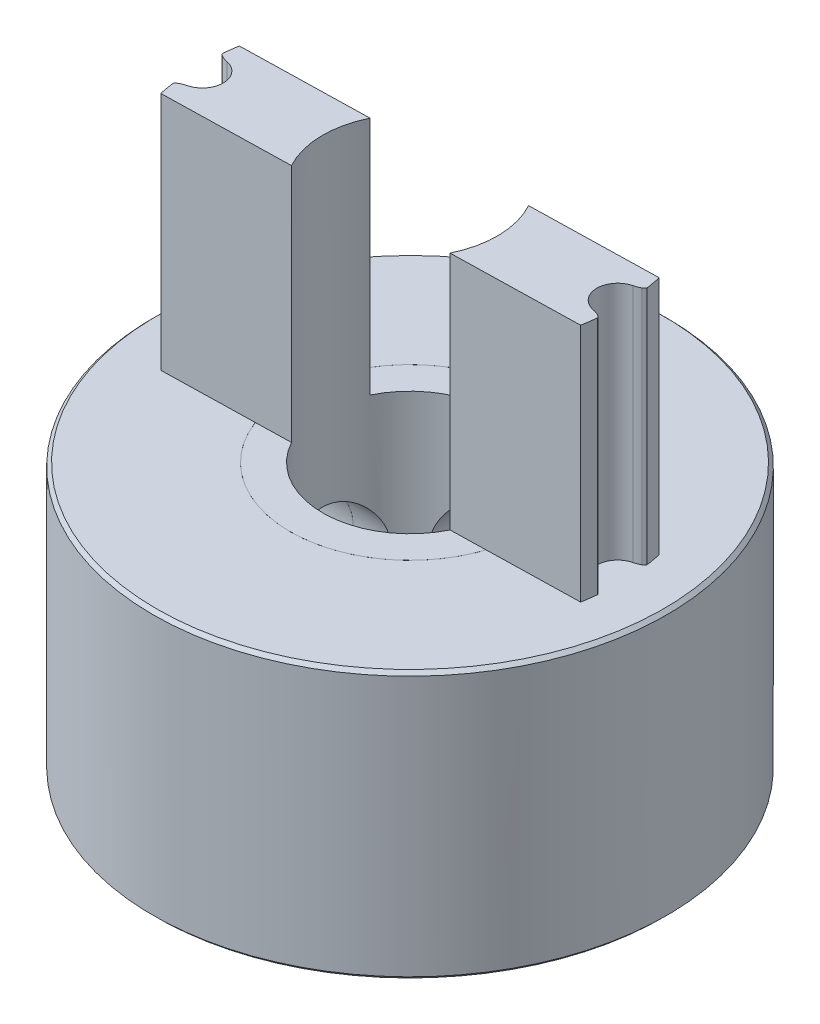
SolidWorks part; units mm, degrees
material "6061 slitina"
ref_plane "Přední rovina" through (0, 0, 0) normal (0, 0, 1) x (1, 0, 0)
ref_plane "Horní rovina" through (0, 0, 0) normal (0, 1, 0) x (1, 0, 0)
ref_plane "Pravá rovina" through (0, 0, 0) normal (1, 0, 0) x (0, 0, -1)
sketch "Skica1" plane through (0, 0, 0) normal (0, 1, 0) x (1, 0, 0)
  circle A0 centre (0, 0) radius 2.5
  arc B0 (-5.7301, 1.0983) -> (-5.3872, 2.2403) centre (-5.6803, 1.7058) ccw
  arc B1 (-5.7301, 1.0983) -> (-5.922, 1.0859) centre (-5.7841, 0.4401) ccw
  arc B2 (-5.922, 1.0859) -> (-6.0197, 1.0387) centre (-5.8743, 0.8624) ccw
  arc B3 (-6.0197, 1.0387) -> (-6.0791, 0.6004) centre (0, 0) ccw
  arc B4 (-6.0791, 0.6004) -> (-5.9974, 0.5289) centre (-5.892, 0.7317) ccw
  arc B5 (-5.9974, 0.5289) -> (-5.8158, 0.466) centre (-5.6927, 1.1148) ccw
  arc B6 (-5.7891, -0.7262) -> (-5.8158, 0.466) centre (-5.9294, -0.133) ccw
  arc B7 (-5.7891, -0.7262) -> (-5.9677, -0.7972) centre (-5.637, -1.3689) ccw
  arc B8 (-5.9677, -0.7972) -> (-6.0461, -0.8723) centre (-5.8532, -0.9951) ccw
  arc B9 (-6.0461, -0.8723) -> (-5.9671, -1.3075) centre (0, 0) ccw
  arc B10 (-5.9671, -1.3075) -> (-5.8673, -1.3503) centre (-5.8297, -1.1248) ccw
  arc B11 (-5.8673, -1.3503) -> (-5.6751, -1.354) centre (-5.7586, -0.6989) ccw
  arc B12 (-5.2813, -2.4796) -> (-5.6751, -1.354) centre (-5.5981, -1.9587) ccw
  arc B13 (-5.2813, -2.4796) -> (-5.4293, -2.6023) centre (-4.9381, -3.0438) ccw
  arc B14 (-5.4293, -2.6023) -> (-5.4806, -2.698) centre (-5.2593, -2.7551) ccw
  arc B15 (-5.4806, -2.698) -> (-5.271, -3.0875) centre (0, 0) ccw
  arc B16 (-5.271, -3.0875) -> (-5.1629, -3.0973) centre (-5.1968, -2.8713) ccw
  arc B17 (-5.1629, -3.0973) -> (-4.979, -3.0415) centre (-5.2608, -2.4442) ccw
  arc B18 (-4.2566, -3.9902) -> (-4.979, -3.0415) centre (-4.7188, -3.5928) ccw
  arc B19 (-4.2566, -3.9902) -> (-4.3594, -4.1527) centre (-3.7559, -4.4208) ccw
  arc B20 (-4.3594, -4.1527) -> (-4.3786, -4.2595) centre (-4.1505, -4.2455) ccw
  arc B21 (-4.3786, -4.2595) -> (-4.059, -4.5652) centre (0, 0) ccw
  arc B22 (-4.059, -4.5652) -> (-3.9531, -4.5412) centre (-4.0552, -4.3366) ccw
  arc B23 (-3.9531, -4.5412) -> (-3.7954, -4.4312) centre (-4.248, -3.9503) ccw
  arc B24 (-2.8152, -5.1103) -> (-3.7954, -4.4312) centre (-3.3776, -4.8751) ccw
  arc B25 (-2.8152, -5.1103) -> (-2.8628, -5.2965) centre (-2.2059, -5.3651) ccw
  arc B26 (-2.8628, -5.2965) -> (-2.8481, -5.4041) centre (-2.6354, -5.3203) ccw
  arc B27 (-2.8481, -5.4041) -> (-2.4496, -5.596) centre (0, 0) ccw
  arc B28 (-2.4496, -5.596) -> (-2.3563, -5.5405) centre (-2.5166, -5.3775) ccw
  arc B29 (-2.3563, -5.5405) -> (-2.2403, -5.3872) centre (-2.8194, -5.0696) ccw
  arc B30 (-1.0983, -5.7301) -> (-2.2403, -5.3872) centre (-1.7058, -5.6803) ccw
  arc B31 (-1.0983, -5.7301) -> (-1.0859, -5.922) centre (-0.4401, -5.7841) ccw
  arc B32 (-1.0859, -5.922) -> (-1.0387, -6.0197) centre (-0.8624, -5.8743) ccw
  arc B33 (-1.0387, -6.0197) -> (-0.6004, -6.0791) centre (0, 0) ccw
  arc B34 (-0.6004, -6.0791) -> (-0.5289, -5.9974) centre (-0.7317, -5.892) ccw
  arc B35 (-0.5289, -5.9974) -> (-0.466, -5.8158) centre (-1.1148, -5.6927) ccw
  arc B36 (0.7262, -5.7891) -> (-0.466, -5.8158) centre (0.133, -5.9294) ccw
  arc B37 (0.7262, -5.7891) -> (0.7972, -5.9677) centre (1.3689, -5.637) ccw
  arc B38 (0.7972, -5.9677) -> (0.8723, -6.0461) centre (0.9951, -5.8532) ccw
  arc B39 (0.8723, -6.0461) -> (1.3075, -5.9671) centre (0, 0) ccw
  arc B40 (1.3075, -5.9671) -> (1.3503, -5.8673) centre (1.1248, -5.8297) ccw
  arc B41 (1.3503, -5.8673) -> (1.354, -5.6751) centre (0.6989, -5.7586) ccw
  arc B42 (2.4796, -5.2813) -> (1.354, -5.6751) centre (1.9587, -5.5981) ccw
  arc B43 (2.4796, -5.2813) -> (2.6023, -5.4293) centre (3.0438, -4.9381) ccw
  arc B44 (2.6023, -5.4293) -> (2.698, -5.4806) centre (2.7551, -5.2593) ccw
  arc B45 (2.698, -5.4806) -> (3.0875, -5.271) centre (0, 0) ccw
  arc B46 (3.0875, -5.271) -> (3.0973, -5.1629) centre (2.8713, -5.1968) ccw
  arc B47 (3.0973, -5.1629) -> (3.0415, -4.979) centre (2.4442, -5.2608) ccw
  arc B48 (3.9902, -4.2566) -> (3.0415, -4.979) centre (3.5928, -4.7188) ccw
  arc B49 (3.9902, -4.2566) -> (4.1527, -4.3594) centre (4.4208, -3.7559) ccw
  arc B50 (4.1527, -4.3594) -> (4.2595, -4.3786) centre (4.2455, -4.1505) ccw
  arc B51 (4.2595, -4.3786) -> (4.5652, -4.059) centre (0, 0) ccw
  arc B52 (4.5652, -4.059) -> (4.5412, -3.9531) centre (4.3366, -4.0552) ccw
  arc B53 (4.5412, -3.9531) -> (4.4312, -3.7954) centre (3.9503, -4.248) ccw
  arc B54 (5.1103, -2.8152) -> (4.4312, -3.7954) centre (4.8751, -3.3776) ccw
  arc B55 (5.1103, -2.8152) -> (5.2965, -2.8628) centre (5.3651, -2.2059) ccw
  arc B56 (5.2965, -2.8628) -> (5.4041, -2.8481) centre (5.3203, -2.6354) ccw
  arc B57 (5.4041, -2.8481) -> (5.596, -2.4496) centre (0, 0) ccw
  arc B58 (5.596, -2.4496) -> (5.5405, -2.3563) centre (5.3775, -2.5166) ccw
  arc B59 (5.5405, -2.3563) -> (5.3872, -2.2403) centre (5.0696, -2.8194) ccw
  arc B60 (5.7301, -1.0983) -> (5.3872, -2.2403) centre (5.6803, -1.7058) ccw
  arc B61 (5.7301, -1.0983) -> (5.922, -1.0859) centre (5.7841, -0.4401) ccw
  arc B62 (5.922, -1.0859) -> (6.0197, -1.0387) centre (5.8743, -0.8624) ccw
  arc B63 (6.0197, -1.0387) -> (6.0791, -0.6004) centre (0, 0) ccw
  arc B64 (6.0791, -0.6004) -> (5.9974, -0.5289) centre (5.892, -0.7317) ccw
  arc B65 (5.9974, -0.5289) -> (5.8158, -0.466) centre (5.6927, -1.1148) ccw
  arc B66 (5.7891, 0.7262) -> (5.8158, -0.466) centre (5.9294, 0.133) ccw
  arc B67 (5.7891, 0.7262) -> (5.9677, 0.7972) centre (5.637, 1.3689) ccw
  arc B68 (5.9677, 0.7972) -> (6.0461, 0.8723) centre (5.8532, 0.9951) ccw
  arc B69 (6.0461, 0.8723) -> (5.9671, 1.3075) centre (0, 0) ccw
  arc B70 (5.9671, 1.3075) -> (5.8673, 1.3503) centre (5.8297, 1.1248) ccw
  arc B71 (5.8673, 1.3503) -> (5.6751, 1.354) centre (5.7586, 0.6989) ccw
  arc B72 (5.2813, 2.4796) -> (5.6751, 1.354) centre (5.5981, 1.9587) ccw
  arc B73 (5.2813, 2.4796) -> (5.4293, 2.6023) centre (4.9381, 3.0438) ccw
  arc B74 (5.4293, 2.6023) -> (5.4806, 2.698) centre (5.2593, 2.7551) ccw
  arc B75 (5.4806, 2.698) -> (5.271, 3.0875) centre (0, 0) ccw
  arc B76 (5.271, 3.0875) -> (5.1629, 3.0973) centre (5.1968, 2.8713) ccw
  arc B77 (5.1629, 3.0973) -> (4.979, 3.0415) centre (5.2608, 2.4442) ccw
  arc B78 (4.2566, 3.9902) -> (4.979, 3.0415) centre (4.7188, 3.5928) ccw
  arc B79 (4.2566, 3.9902) -> (4.3594, 4.1527) centre (3.7559, 4.4208) ccw
  arc B80 (4.3594, 4.1527) -> (4.3786, 4.2595) centre (4.1505, 4.2455) ccw
  arc B81 (4.3786, 4.2595) -> (4.059, 4.5652) centre (0, 0) ccw
  arc B82 (4.059, 4.5652) -> (3.9531, 4.5412) centre (4.0552, 4.3366) ccw
  arc B83 (3.9531, 4.5412) -> (3.7954, 4.4312) centre (4.248, 3.9503) ccw
  arc B84 (2.8152, 5.1103) -> (3.7954, 4.4312) centre (3.3776, 4.8751) ccw
  arc B85 (2.8152, 5.1103) -> (2.8628, 5.2965) centre (2.2059, 5.3651) ccw
  arc B86 (2.8628, 5.2965) -> (2.8481, 5.4041) centre (2.6354, 5.3203) ccw
  arc B87 (2.8481, 5.4041) -> (2.4496, 5.596) centre (0, 0) ccw
  arc B88 (2.4496, 5.596) -> (2.3563, 5.5405) centre (2.5166, 5.3775) ccw
  arc B89 (2.3563, 5.5405) -> (2.2403, 5.3872) centre (2.8194, 5.0696) ccw
  arc B90 (1.0983, 5.7301) -> (2.2403, 5.3872) centre (1.7058, 5.6803) ccw
  arc B91 (1.0983, 5.7301) -> (1.0859, 5.922) centre (0.4401, 5.7841) ccw
  arc B92 (1.0859, 5.922) -> (1.0387, 6.0197) centre (0.8624, 5.8743) ccw
  arc B93 (1.0387, 6.0197) -> (0.6004, 6.0791) centre (0, 0) ccw
  arc B94 (0.6004, 6.0791) -> (0.5289, 5.9974) centre (0.7317, 5.892) ccw
  arc B95 (0.5289, 5.9974) -> (0.466, 5.8158) centre (1.1148, 5.6927) ccw
  arc B96 (-0.7262, 5.7891) -> (0.466, 5.8158) centre (-0.133, 5.9294) ccw
  arc B97 (-0.7262, 5.7891) -> (-0.7972, 5.9677) centre (-1.3689, 5.637) ccw
  arc B98 (-0.7972, 5.9677) -> (-0.8723, 6.0461) centre (-0.9951, 5.8532) ccw
  arc B99 (-0.8723, 6.0461) -> (-1.3075, 5.9671) centre (0, 0) ccw
  arc B100 (-1.3075, 5.9671) -> (-1.3503, 5.8673) centre (-1.1248, 5.8297) ccw
  arc B101 (-1.3503, 5.8673) -> (-1.354, 5.6751) centre (-0.6989, 5.7586) ccw
  arc B102 (-2.4796, 5.2813) -> (-1.354, 5.6751) centre (-1.9587, 5.5981) ccw
  arc B103 (-2.4796, 5.2813) -> (-2.6023, 5.4293) centre (-3.0438, 4.9381) ccw
  arc B104 (-2.6023, 5.4293) -> (-2.698, 5.4806) centre (-2.7551, 5.2593) ccw
  arc B105 (-2.698, 5.4806) -> (-3.0875, 5.271) centre (0, 0) ccw
  arc B106 (-3.0875, 5.271) -> (-3.0973, 5.1629) centre (-2.8713, 5.1968) ccw
  arc B107 (-3.0973, 5.1629) -> (-3.0415, 4.979) centre (-2.4442, 5.2608) ccw
  arc B108 (-3.9902, 4.2566) -> (-3.0415, 4.979) centre (-3.5928, 4.7188) ccw
  arc B109 (-3.9902, 4.2566) -> (-4.1527, 4.3594) centre (-4.4208, 3.7559) ccw
  arc B110 (-4.1527, 4.3594) -> (-4.2595, 4.3786) centre (-4.2455, 4.1505) ccw
  arc B111 (-4.2595, 4.3786) -> (-4.5652, 4.059) centre (0, 0) ccw
  arc B112 (-4.5652, 4.059) -> (-4.5412, 3.9531) centre (-4.3366, 4.0552) ccw
  arc B113 (-4.5412, 3.9531) -> (-4.4312, 3.7954) centre (-3.9503, 4.248) ccw
  arc B114 (-5.1103, 2.8152) -> (-4.4312, 3.7954) centre (-4.8751, 3.3776) ccw
  arc B115 (-5.1103, 2.8152) -> (-5.2965, 2.8628) centre (-5.3651, 2.2059) ccw
  arc B116 (-5.2965, 2.8628) -> (-5.4041, 2.8481) centre (-5.3203, 2.6354) ccw
  arc B117 (-5.4041, 2.8481) -> (-5.596, 2.4496) centre (0, 0) ccw
  arc B118 (-5.596, 2.4496) -> (-5.5405, 2.3563) centre (-5.3775, 2.5166) ccw
  arc B119 (-5.5405, 2.3563) -> (-5.3872, 2.2403) centre (-5.0696, 2.8194) ccw
  dimension "D1" = 5
sketch_block_instance "Blok1-1"
sketch_block "Blok1"
extrude "Přidat vysunutím1" add sketch "Skica1" along normal blind 7 from offset 7.8
sketch "Skica2" plane through (0, 7.8, 0) normal (0, -1, 0) x (1, 0, 0)
  circle A0 centre (0, 0) radius 3.5
  circle A1 centre (0, 0) radius 2.5 construction
  circle A2 centre (0, 0) radius 2.5
  dimension "D1" = 7
extrude "Přidat vysunutím2" add sketch "Skica2" along normal blind 7.8
sketch "Skica3" plane through (0, 14.8, 0) normal (0, 1, 0) x (1, 0, 0)
  circle A0 centre (0, 0) radius 3.5
  circle A1 centre (0, 0) radius 2.5 construction
  circle A2 centre (0, 0) radius 2.5
  dimension "D1" = 7
sketch "Skica5" plane through (0, 16, 0) normal (0, 1, 0) x (1, 0, 0)
  circle A0 centre (0, 0) radius 7.5
  circle A3 centre (0, 0) radius 3.5 construction
  circle A4 centre (0, 0) radius 3.5
  dimension "D1" = 15
sketch "Skica6" plane through (0, 0, 0) normal (0, -1, 0) x (1, 0, 0)
  circle A0 centre (0, 0) radius 7.5
  circle A1 centre (0, 0) radius 3.5 construction
  circle A2 centre (0, 0) radius 3.5
  circle A3 centre (0, 0) radius 7.5 construction
extrude "Přidat vysunutím5" add sketch "Skica6" against normal up to surface (7.8 mm away) separate body up to face at (0, 7.8, 0)
chamfer "Zkosení3" distance 0.1 angle 45 2 edges at (0, 0, -7.5) (0, 7.8, 7.5)
sketch "Sketch7" plane through (0, 0, 0) normal (0, -1, 0) x (1, 0, 0)
  circle A1 centre (0, 0) radius 4.05
  dimension "D1" = 8.1
sketch "Sketch8" plane through (0, 16, 0) normal (0, 1, 0) x (1, 0, 0)
  circle A0 centre (0, 0) radius 6.65
ref_plane "Plane1" through (0, 0, -7.5) normal (0, 0, -1) x (-1, 0, 0)
ref_plane "Plane2" through (-7.5, 0, 0) normal (-1, 0, 0) x (0, 0, 1)
sketch "Sketch19" plane through (0, 0, -7.5) normal (0, 0, -1) x (-1, 0, 0)
  line L0 (0, 0.1) -> (0, 7.7)
  line L1 (7.5, 0.1) -> (-7.5, 0.1) construction
  line L2 (7.5, 7.7) -> (-7.5, 7.7) construction
  circle A0 centre (0, 3.9) radius 1.5
extrude "Cut-Extrude6" cut sketch "Sketch19" against normal blind 8 contours A0
sketch "Sketch20" plane through (-7.5, 0, 0) normal (-1, 0, 0) x (0, 0, 1)
  line L0 (0, 0.1) -> (0, 7.7)
  line L1 (-7.5, 0.1) -> (7.5, 0.1) construction
  line L2 (7.5, 7.7) -> (-7.5, 7.7) construction
  circle A0 centre (0, 3.9) radius 1.5
extrude "Cut-Extrude7" cut sketch "Sketch20" against normal blind 8 contours A0
sketch "Sketch21" plane through (0, 16, 0) normal (0, 1, 0) x (1, 0, 0)
  circle A0 centre (0, 0) radius 2.55
extrude "Cut-Extrude8" cut sketch "Sketch21" against normal blind 30
sketch "Sketch23" plane through (0, 14.8, 0) normal (0, 1, 0) x (1, 0, 0)
  line L0 (-5.9671, -1.3075) -> (6.0197, -1.0387)
  line L1 (5.9671, 1.3075) -> (-6.0197, 1.0387)
  line L2 (-6.0197, 1.0387) -> (-9.0718, 9.5953)
  line L3 (-9.0718, 9.5953) -> (10.3249, 9.8125)
  line L4 (10.3249, 9.8125) -> (9.1302, -12.0603)
  line L5 (9.1302, -12.0603) -> (-8.8312, -11.8866)
  line L6 (-8.8312, -11.8866) -> (-5.9671, -1.3075)
  line L7 (6.0197, -1.0387) -> (7.9079, 0.5339)
  line L8 (7.9079, 0.5339) -> (5.9671, 1.3075)
extrude "Cut-Extrude9" cut sketch "Sketch23" against normal blind 7
